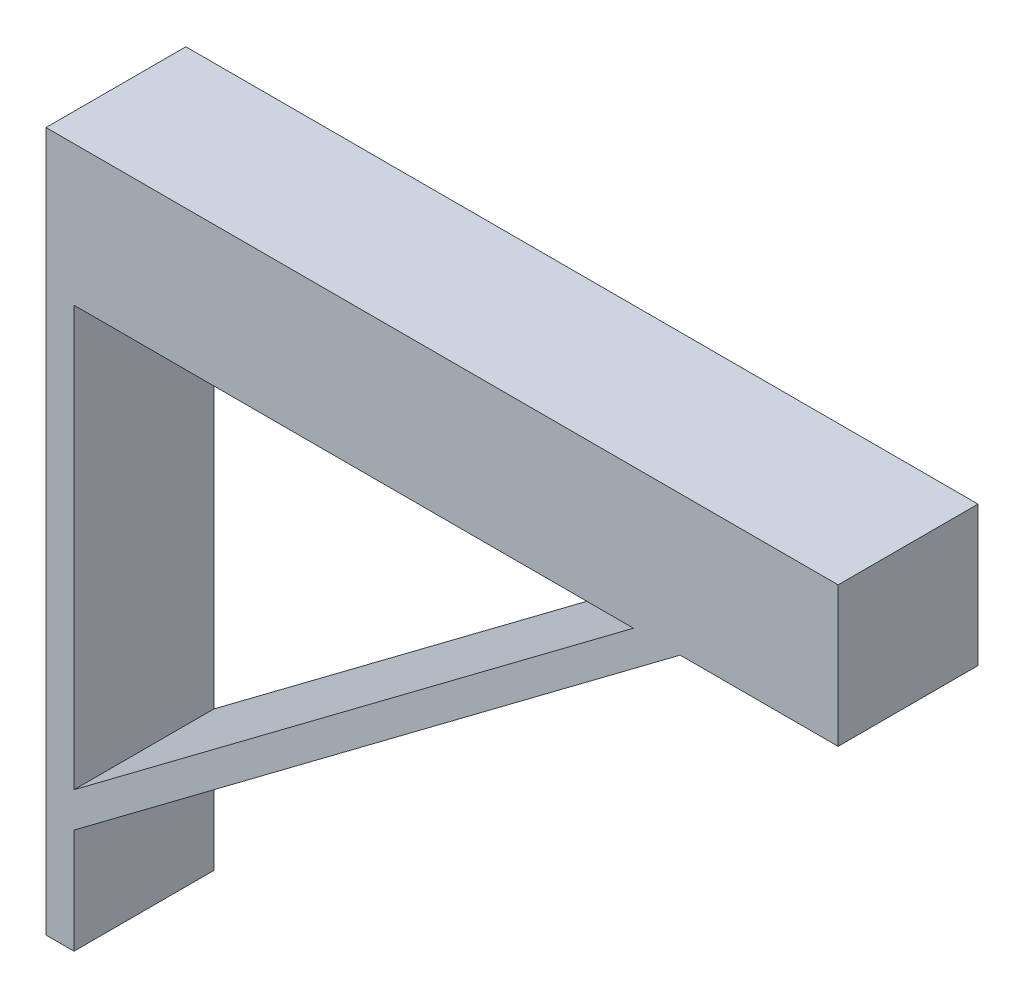
SolidWorks part; units mm, degrees
ref_plane "Front Plane" through (0, 0, 0) normal (0, 0, 1) x (1, 0, 0)
ref_plane "Top Plane" through (0, 0, 0) normal (0, 1, 0) x (1, 0, 0)
ref_plane "Right Plane" through (0, 0, 0) normal (1, 0, 0) x (0, 0, -1)
sketch "Sketch1" plane through (0, 0, 0) normal (0, 0, 1) x (1, 0, 0)
  line L0 (-43.956, -46.4835) -> (36.044, 13.5165)
  line L1 (-47.956, 33.5165) -> (-43.956, 33.5165)
  line L2 (-47.956, 33.5165) -> (-47.956, -66.4835)
  line L3 (-47.956, -66.4835) -> (-43.956, -66.4835)
  line L4 (-43.956, 13.5165) -> (-43.956, -46.4835)
  line L5 (-43.956, 33.5165) -> (65.304, 33.5165)
  line L6 (-43.956, 33.5165) -> (-43.956, 13.5165)
  line L7 (-43.956, 13.5165) -> (36.044, 13.5165)
  line L8 (65.304, 33.5165) -> (65.304, 13.5165)
  line L9 (42.7106, 13.5165) -> (-43.956, -51.4835)
  line L10 (-43.956, -51.4835) -> (-43.956, -66.4835)
  line L11 (42.7106, 13.5165) -> (65.304, 13.5165)
  dimension "D1" = 100
  dimension "D2" = 109.26
  dimension "D3" = 60
  dimension "D4" = 20
  dimension "D5" = 4
  dimension "D6" = 4
  dimension "D7" = 80
extrude "Boss-Extrude1" add sketch "Sketch1" along normal blind 20
